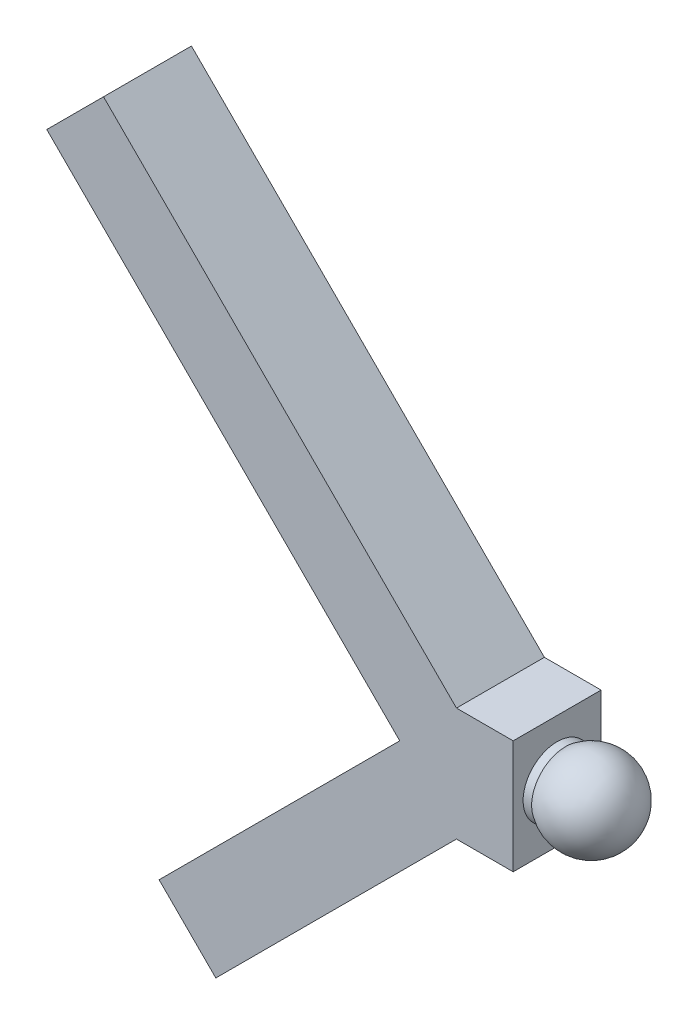
SolidWorks part; units mm, degrees
ref_plane "Front Plane" through (0, 0, 0) normal (0, 0, 1) x (1, 0, 0)
ref_plane "Top Plane" through (0, 0, 0) normal (0, 1, 0) x (1, 0, 0)
ref_plane "Right Plane" through (0, 0, 0) normal (1, 0, 0) x (0, 0, -1)
sketch "Sketch3" plane through (0, 0, 0) normal (0, 0, 1) x (1, 0, 0)
  line L0 (-2.5, 5) -> (2.5, 5)
  line L5 (-2.5, 5) -> (-33.6127, 36.1127)
  line L6 (-33.6127, 36.1127) -> (-38.6127, 31.1127)
  line L7 (-38.6127, 31.1127) -> (-7.5, 0)
  line L8 (-7.5, 0) -> (-28.7132, -21.2132)
  line L9 (-28.7132, -21.2132) -> (-23.7132, -26.2132)
  line L10 (-23.7132, -26.2132) -> (-2.5, -5)
  line L11 (2.5, 5) -> (2.5, -5)
  line L12 (2.5, -5) -> (-2.5, -5)
  line L15 (2.5, 1.5) -> (2.5, -1.5)
  point P12 (2.5, 0)
  point P16 (0, -5)
  point P17 (0, 0)
  dimension "D1" = 90
  dimension "D2" = 5
  dimension "D3" = 7.5
  dimension "D4" = 10
  dimension "D6" = 44
  dimension "D7" = 30
extrude "Boss-Extrude3" add sketch "Sketch3" along normal blind 7.75
sketch "Sketch4" plane through (2.5, 0, 0) normal (1, 0, 0) x (0, 0, -1)
  circle A0 centre (-3.875, 0) radius 3
  dimension "D1" = 6
extrude "Boss-Extrude4" add sketch "Sketch4" along normal blind 3
sketch "Sketch5" plane through (5.5, 0, 0) normal (1, 0, 0) x (0, 0, -1)
  line L0 (-3.875, 3.75) -> (-3.875, -3.75)
  line L1 (-3.875, 4.1357) -> (-3.875, -4.4465) construction
  arc A0 (-3.875, 3.75) -> (-3.875, -3.75) centre (-3.875, 0) ccw
  point P6 (0, 0)
  dimension "D1" = 3.75
revolve "Revolve1" add sketch "Sketch5" angle 360 about L1
